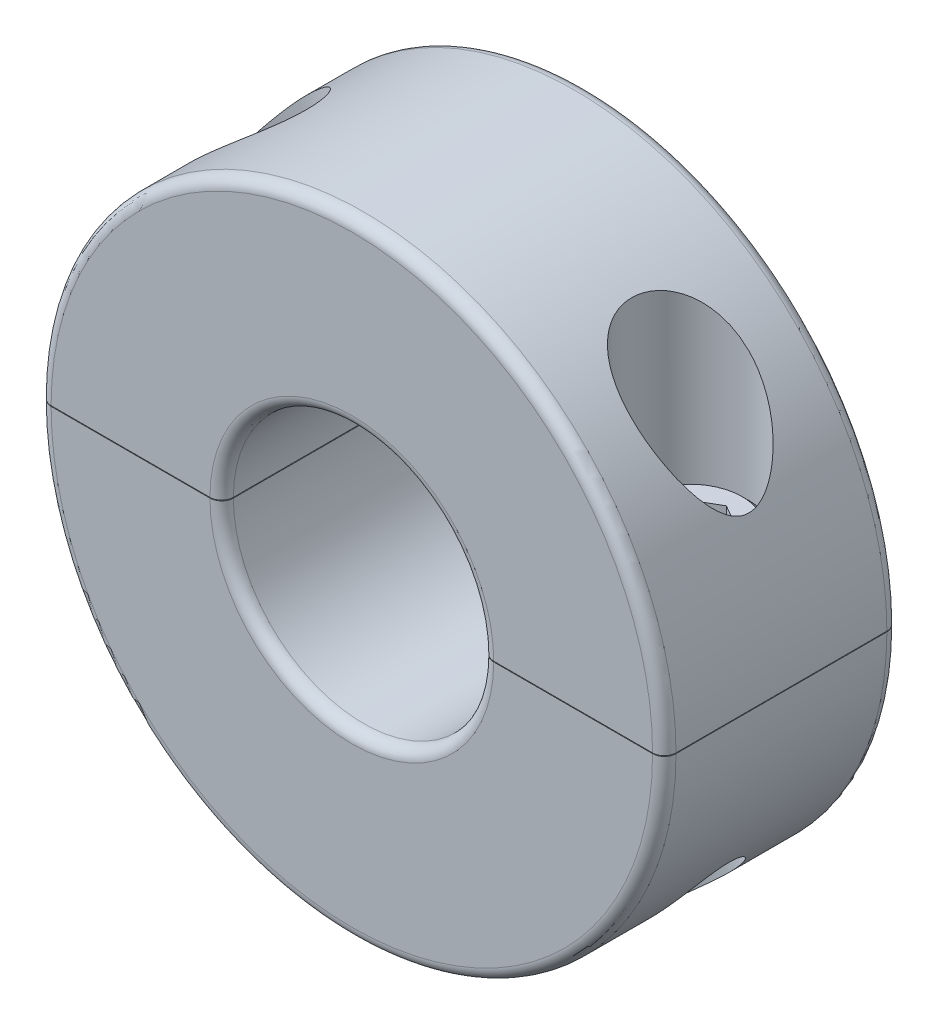
SolidWorks part; units mm, degrees
ref_plane "Front Plane" through (0, 0, 0) normal (0, 0, 1) x (1, 0, 0)
ref_plane "Top Plane" through (0, 0, 0) normal (0, 1, 0) x (1, 0, 0)
ref_plane "Right Plane" through (0, 0, 0) normal (1, 0, 0) x (0, 0, -1)
sketch "Sketch1" plane through (0, 0, 0) normal (0, 0, 1) x (1, 0, 0)
  line L0 (-12, 0) -> (-5, 0) construction
  line L1 (-12, 0.012) -> (-5, 0.012)
  line L2 (-12, -0.012) -> (-5, -0.012)
  line L3 (5, 0.012) -> (12, 0.012)
  line L4 (5, -0.012) -> (12, -0.012)
  line L5 (0, 0) -> (0, 12) construction
  circle A0 centre (0, 0) radius 12 construction
  circle A1 centre (0, 0) radius 5 construction
  arc A2 (-12, 0.012) -> (12, 0.012) centre (0, 0.012) cw
  arc A3 (-12, -0.012) -> (12, -0.012) centre (0, -0.012) ccw
  arc A4 (-5, 0.012) -> (5, 0.012) centre (0, 0.012) cw
  arc A5 (-5, -0.012) -> (5, -0.012) centre (0, -0.012) ccw
  point P4 (12, 0)
  dimension "Bore Dia" = 10
  dimension "OD" = 24
  dimension "Separation" = 0.024
extrude "Extrude1" add sketch "Sketch1" along normal mid plane 9
sketch "Sketch4" plane through (0, 0, 0) normal (0, 0, 1) x (1, 0, 0)
  line L0 (-8.5, 12.012) -> (-6.25, 12.012)
  line L1 (-6.25, 12.012) -> (-6.25, 0.762)
  line L2 (-6.25, 0.762) -> (-7, 0.762)
  line L3 (-7, 0.762) -> (-7, -12.012)
  line L4 (-7, -12.012) -> (-8.5, -12.012)
  line L5 (-8.5, -12.012) -> (-8.5, 12.012)
  line L6 (-6.25, 3.762) -> (-10.75, 3.762) construction
  line L7 (-8.5, 12.012) -> (-8.5, 14.552) construction
  line L8 (-6.25, 12.012) -> (0, 12.012) construction
  line L9 (0, -12.012) -> (-7, -12.012) construction
  line L10 (-12, 0) -> (-5, 0) construction
  line L11 (-12, 0.012) -> (-5, 0.012) construction
  circle A0 centre (0, 0) radius 12 construction
  arc A1 (12, 0.012) -> (-12, 0.012) centre (0, 0.012) ccw construction
  circle A2 centre (0, 0) radius 5 construction
  arc A3 (-12, -0.012) -> (12, -0.012) centre (0, -0.012) ccw construction
  point P13 (-8.5, 0)
  point P19 (-8.5, 0)
  point P20 (-8.5, 3.762)
  dimension "D1" = 3
  dimension "D2" = 7
  dimension "D3" = 0.75
  dimension "D4" = 4.5
  dimension "D5" = 2.54
  dimension "Screw Dia" = 3
revolve "Cut-Revolve1" cut sketch "Sketch4" angle 360 about L5
sketch "Sketch6" plane through (0, 0, 0) normal (0, 0, 1) x (1, 0, 0)
  line L0 (-8.5, 3.762) -> (-6.25, 3.762)
  line L1 (-6.25, 3.762) -> (-10.75, 3.762) construction
  line L2 (-6.25, 3.762) -> (-6.25, 0.762)
  line L3 (-6.25, 0.762) -> (-7, 0.762)
  line L4 (-7, 0.762) -> (-7, -5.238)
  line L5 (-7, 0.762) -> (-7, -12.012) construction
  line L6 (-7, -5.238) -> (-8.5, -5.238)
  line L7 (-8.5, -12.012) -> (-8.5, 12.012) construction
  line L8 (-8.5, -5.238) -> (-8.5, 3.762)
  line L9 (-7, -5.238) -> (-10, -5.238) construction
  dimension "Head Ht" = 3
  dimension "Screw Lg" = 9
revolve "Revolve1" add sketch "Sketch6" angle 360 about L8
mirror "Mirror1" about plane through (0, 0, 0) normal (1, 0, 0) of "Cut-Revolve1"
sketch "Sketch7" plane through (0, 3.762, 0) normal (0, 1, 0) x (-1, 0, 0)
  line L1 (8.5, -1.3856) -> (9.7, -0.6928)
  line L2 (9.7, -0.6928) -> (9.7, 0.6928)
  line L3 (9.7, 0.6928) -> (8.5, 1.3856)
  line L4 (8.5, 1.3856) -> (7.3, 0.6928)
  line L5 (7.3, 0.6928) -> (7.3, -0.6928)
  line L6 (7.3, -0.6928) -> (8.5, -1.3856)
  circle A0 centre (8.5, 0) radius 1.2 construction
  dimension "D1" = 2.4
extrude "Cut-Extrude2" cut sketch "Sketch7" against normal blind 1.5
mirror "Mirror2" about plane through (0, 0, 0) normal (1, 0, 0) of bodies 149 147
fillet "Fillet1" radius 0.45 4 edges at (0, 5.012, -4.5) (0, 5.012, 4.5) (0, 12.012, -4.5) (0, 12.012, 4.5)
fillet "Fillet2" radius 0.45 4 edges at (0, -12.012, -4.5) (0, -12.012, 4.5) (0, -5.012, -4.5) (0, -5.012, 4.5)
chamfer "Chamfer1" distance 0.254 angle 45 1 edges at (8.5, 3.762, -2.25)
chamfer "Chamfer2" distance 0.254 angle 45 1 edges at (-8.5, 3.762, -2.25)
equation "\"D1@Sketch4\" = \"Screw Dia@Sketch4\""
equation "\"D4@Sketch4\" = \"Screw Dia@Sketch4\"*1.5"
equation "\"D1@Sketch7\" = \"Screw Dia@Sketch4\"*.8"
equation "\"D1@Cut-Extrude2\" = \"Head Ht@Sketch6\"/2"
equation "\"D3@Sketch4\" = \"D1@Sketch4\"*.25"
equation "\"D1@Fillet1\" = \"Width@Extrude1\"*.05"
equation "\"D1@Fillet2\" = \"D1@Fillet1\""
equation "\"Screw Lg@Sketch6\" = \"Head Ht@Sketch6\"*3"
